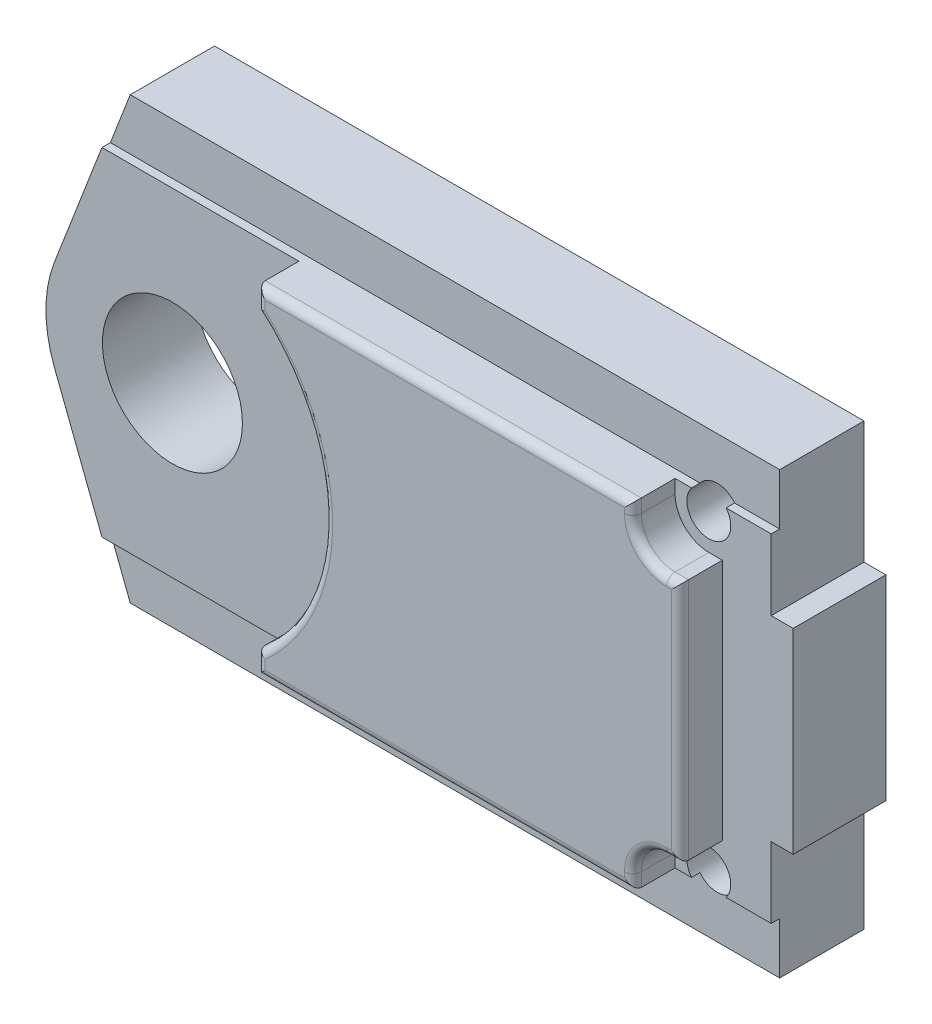
SolidWorks part; units mm, degrees
ref_plane "Front Plane" through (0, 0, 0) normal (0, 0, 1) x (1, 0, 0)
ref_plane "Top Plane" through (0, 0, 0) normal (0, 1, 0) x (1, 0, 0)
ref_plane "Right Plane" through (0, 0, 0) normal (1, 0, 0) x (0, 0, -1)
sketch "Sketch1" plane through (0, 0, 0) normal (0, 0, 1) x (1, 0, 0)
  line L0 (0, 0) -> (41.4105, 0) construction
  line L1 (35.5, 5.8) -> (36.8, 5.8)
  line L2 (35.5, 13.05) -> (-3.0002, 13.05)
  line L3 (35.5, 13.05) -> (35.5, 5.8)
  line L4 (35.5, -13.05) -> (-3.0002, -13.05)
  line L5 (-3.0002, 13.05) -> (-6.9964, 2.7019)
  line L6 (36.8, 5.8) -> (36.8, -5.8)
  line L7 (36.8, -5.8) -> (35.5, -5.8)
  line L8 (35.5, -5.8) -> (35.5, -13.05)
  line L11 (-3.0002, -13.05) -> (-6.9964, -2.7019)
  circle A0 centre (31.8, 9.2) radius 1.3
  circle A1 centre (31.8, -9.2) radius 1.3
  circle A2 centre (0, 0) radius 4.15
  arc A3 (-6.9964, 2.7019) -> (-6.9964, -2.7019) centre (0, 0) ccw
  dimension "D5" = 3.0002
  dimension "D9" = 8.3
  dimension "D10" = 15
  dimension "D14" = 2.6
  dimension "D2" = 35.5
  dimension "D3" = 13.05
  dimension "D4" = 13.05
  dimension "D6" = 1.3
  dimension "D7" = 5.8
  dimension "D8" = 5.8
  dimension "D11" = 3.0002
  dimension "D12" = 3.7
  dimension "D13" = 9.2
extrude "Extrude1" add sketch "Sketch1" along normal blind 5.5
sketch "Sketch2" plane through (0, 0, 5.5) normal (0, 0, 1) x (1, 0, 0)
  line L0 (0, 0) -> (38.1811, 0) construction
  line L1 (7.5, 10) -> (29.8, 10)
  line L2 (32.6, 7.2) -> (32.6, -7.2)
  line L3 (36.8, -5.8) -> (36.8, 5.8) construction
  line L4 (31.8, 7.2) -> (32.6, 7.2)
  line L5 (29.8, 9.2) -> (29.8, 10)
  line L6 (7.5, 10) -> (7.5, 8.7178)
  line L7 (31.8, -7.2) -> (32.6, -7.2)
  line L8 (29.8, -9.2) -> (29.8, -10)
  line L9 (7.5, -10) -> (29.8, -10)
  line L10 (7.5, -10) -> (7.5, -8.7178)
  arc A0 (29.8, 9.2) -> (31.8, 7.2) centre (31.8, 9.2) ccw
  arc A1 (7.5, -8.7178) -> (7.5, 8.7178) centre (0, 0) ccw
  arc A2 (29.8, -9.2) -> (31.8, -7.2) centre (31.8, -9.2) cw
  point P19 (32.6, 0)
  dimension "D1" = 4
  dimension "D4" = 23
  dimension "D2" = 10
  dimension "D3" = 4.2
  dimension "D5" = 7.5
extrude "Extrude2" add sketch "Sketch2" along normal blind 2.5
fillet "Fillet1" radius 0.5 12 edges at (29.8, -9.6, 8) (18.65, -10, 8) (7.5, -9.3589, 8) (11.5, 0, 8) (7.5, 9.3589, 8) (18.65, 10, 8) (29.8, 9.6, 8) (30.3858, 7.7858, 8) (32.2, 7.2, 8) (32.6, 0, 8) (32.2, -7.2, 8) (30.3858, -7.7858, 8)
sketch "Sketch3" plane through (0, 0, 5.5) normal (0, 0, 1) x (1, 0, 0)
  line L1 (-4.178, -10) -> (35.5, -10)
  line L3 (7.5, -10) -> (29.8, -10) construction
  line L4 (-4.178, 10) -> (35.5, 10)
  line L5 (29.8, 10) -> (7.5, 10) construction
  line L9 (35.5, 5.8) -> (35.5, 13.05)
  line L10 (35.5, 13.05) -> (-3.0002, 13.05)
  line L11 (-3.0002, 13.05) -> (-6.9964, 2.7019)
  line L12 (-6.9964, -2.7019) -> (-3.0002, -13.05)
  line L13 (-3.0002, -13.05) -> (35.5, -13.05)
  line L14 (35.5, -13.05) -> (35.5, -5.8)
  line L15 (35.5, -5.8) -> (36.8, -5.8)
  line L16 (36.8, -5.8) -> (36.8, 5.8)
  line L17 (36.8, 5.8) -> (35.5, 5.8)
  line L18 (35.5, 10) -> (35.5, 13.05)
  line L19 (35.5, 13.05) -> (-3.0002, 13.05)
  line L20 (-3.0002, 13.05) -> (-4.178, 10)
  line L21 (-4.178, -10) -> (-3.0002, -13.05)
  line L22 (-3.0002, -13.05) -> (35.5, -13.05)
  line L23 (35.5, -13.05) -> (35.5, -10)
  arc A1 (-6.9964, 2.7019) -> (-6.9964, -2.7019) centre (0, 0) ccw
  dimension "D1" = 0
extrude "Cut-Extrude1" cut sketch "Sketch3" against normal blind 0.5
